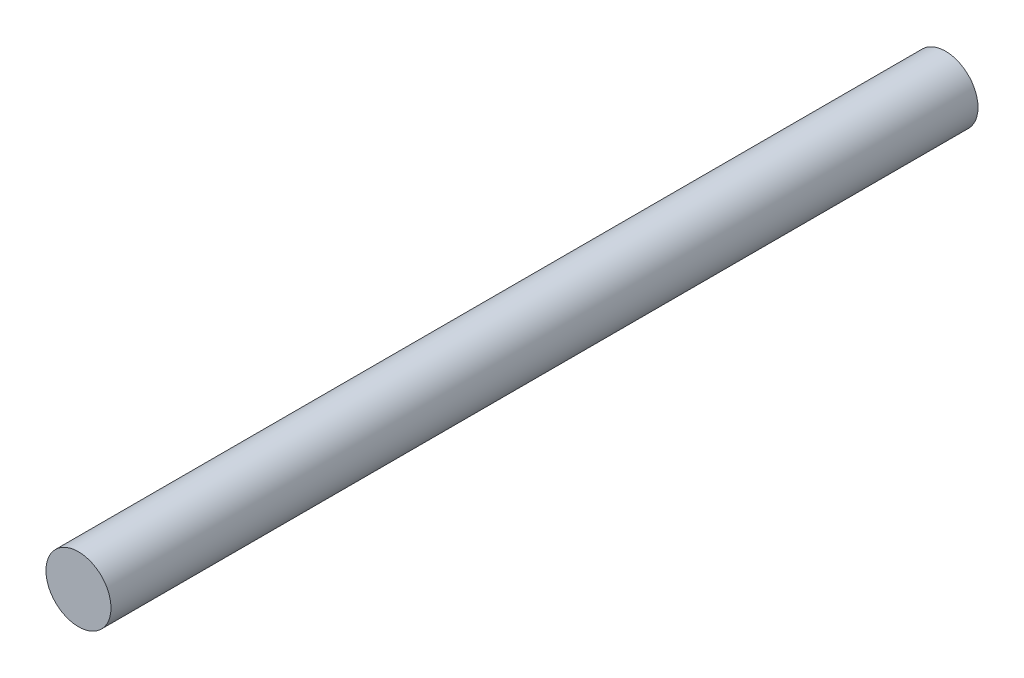
SolidWorks part; units mm, degrees
ref_plane "前视基准面" through (0, 0, 0) normal (0, 0, 1) x (1, 0, 0)
ref_plane "上视基准面" through (0, 0, 0) normal (0, 1, 0) x (1, 0, 0)
ref_plane "右视基准面" through (0, 0, 0) normal (1, 0, 0) x (0, 0, -1)
sketch "草图1" plane through (0, 0, 0) normal (0, 0, 1) x (1, 0, 0)
  circle A0 centre (0, 0) radius 1.5
  dimension "D1" = 3
extrude "凸台-拉伸1" add sketch "草图1" along normal blind 40 contours A0
